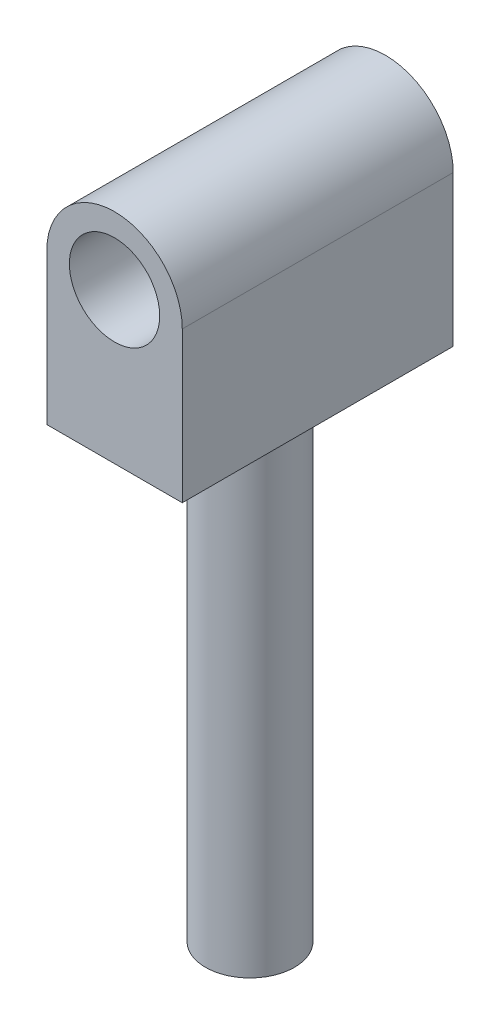
SolidWorks part; units mm, degrees
material "ABS"
ref_plane "Front Plane" through (0, 0, 0) normal (0, 0, 1) x (1, 0, 0)
ref_plane "Top Plane" through (0, 0, 0) normal (0, 1, 0) x (1, 0, 0)
ref_plane "Right Plane" through (0, 0, 0) normal (1, 0, 0) x (0, 0, -1)
sketch "Sketch1" plane through (0, 0, 0) normal (0, 0, 1) x (1, 0, 0)
  line L0 (-11.43, 0) -> (-11.43, -25.4)
  line L1 (11.43, 0) -> (11.43, -25.4)
  line L2 (11.43, -25.4) -> (-11.43, -25.4)
  arc A1 (11.43, 0) -> (-11.43, 0) centre (0, 0) ccw
extrude "Boss-Extrude1" add sketch "Sketch1" along normal blind 45.72
sketch "Sketch2" plane through (0, 0, 45.72) normal (0, 0, 1) x (1, 0, 0)
  circle A0 centre (0, 0) radius 7.62
extrude "Cut-Extrude1" cut sketch "Sketch2" against normal blind 10.414
sketch "Sketch3" plane through (0, 0, 45.72) normal (0, 0, 1) x (1, 0, 0)
  circle A0 centre (0, 0) radius 7.62
extrude "Cut-Extrude2" cut sketch "Sketch3" against normal blind 76.2
sketch "Sketch4" plane through (0, -25.4, 0) normal (0, -1, 0) x (1, 0, 0)
  line L0 (0, 0) -> (0, 50.4535)
  line L1 (11.43, 45.72) -> (11.43, 0)
  line L3 (11.43, 22.86) -> (-16.7457, 22.86)
  line L4 (-11.43, 45.72) -> (11.43, 45.72) construction
  line L5 (0, 45.72) -> (0, 0)
  circle A0 centre (0, 22.86) radius 7.5141
extrude "Boss-Extrude2" add sketch "Sketch4" along normal blind 81.28 contours L0 A0 L3 | L3 A0 L5 | L5 A0 L3 | L3 A0 L0
